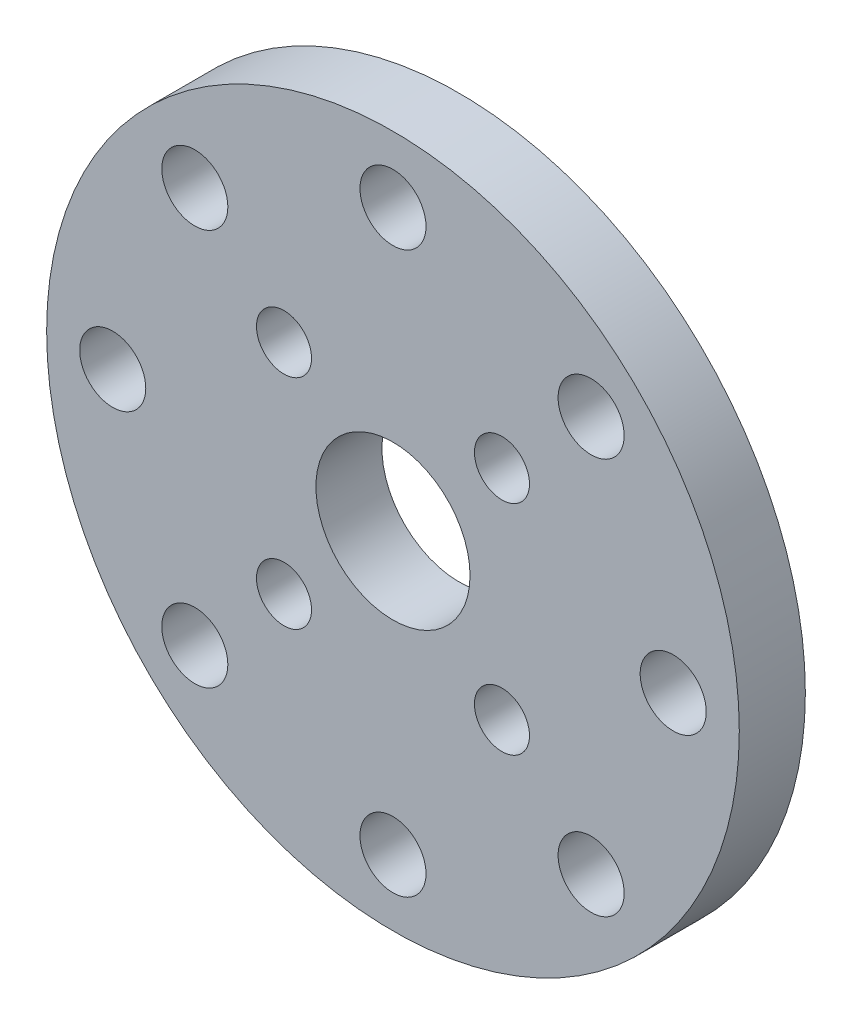
SolidWorks part; units mm, degrees
ref_plane "Alzado" through (0, 0, 0) normal (0, 0, 1) x (1, 0, 0)
ref_plane "Planta" through (0, 0, 0) normal (0, 1, 0) x (1, 0, 0)
ref_plane "Vista lateral" through (0, 0, 0) normal (1, 0, 0) x (0, 0, -1)
sketch "Model" plane through (0, 0, 0) normal (0, 0, 1) x (1, 0, 0)
  circle A0 centre (20.2464, 297.2754) radius 1.5
  circle A1 centre (7.5185, 284.5475) radius 1.5
  circle A2 centre (20.2464, 271.8196) radius 1.5
  circle A3 centre (32.9743, 284.5475) radius 1.5
  circle A4 centre (15.2967, 289.4972) radius 1.25
  circle A5 centre (15.2967, 279.5977) radius 1.25
  circle A6 centre (25.1961, 279.5977) radius 1.25
  circle A7 centre (25.1961, 289.4972) radius 1.25
  circle A8 centre (20.2464, 284.5475) radius 3.5
  circle A9 centre (11.2464, 293.5475) radius 1.5
  circle A10 centre (11.2464, 275.5475) radius 1.5
  circle A11 centre (29.2464, 275.5475) radius 1.5
  circle A12 centre (29.2464, 293.5475) radius 1.5
  circle A13 centre (20.2464, 284.5475) radius 15.73
extrude "Saliente-Extruir1" add sketch "Model" along normal blind 3
